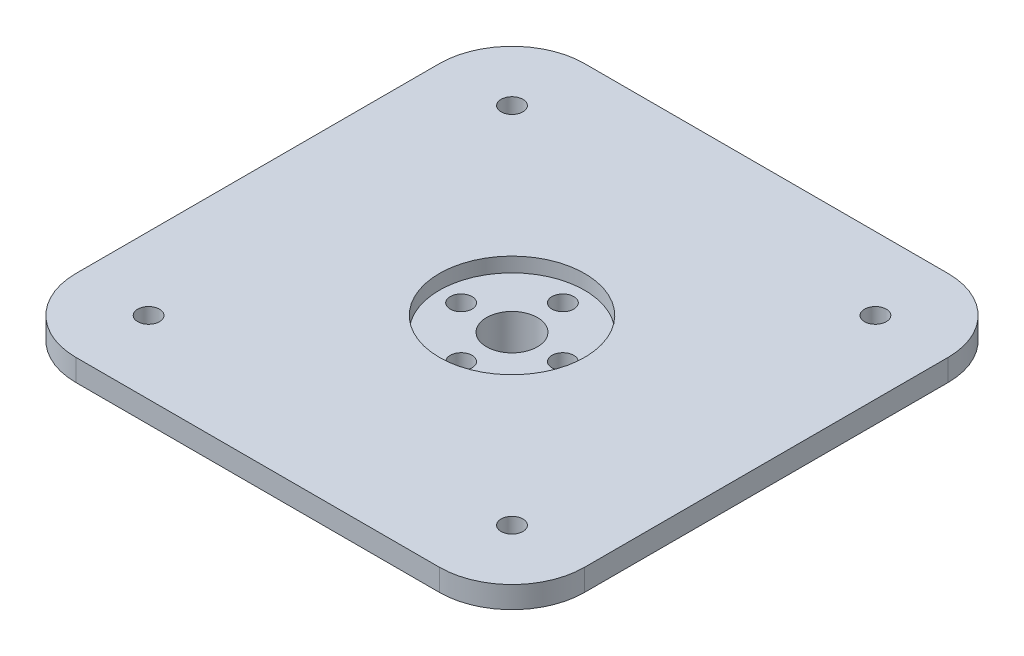
SolidWorks part; units mm, degrees
material "聚脂树脂"
ref_plane "前视基准面" through (0, 0, 0) normal (0, 0, 1) x (1, 0, 0)
ref_plane "上视基准面" through (0, 0, 0) normal (0, 1, 0) x (1, 0, 0)
ref_plane "右视基准面" through (0, 0, 0) normal (1, 0, 0) x (0, 0, -1)
other "Configuration Table"
sketch "草图1" plane through (0, 0, 0) normal (0, 1, 0) x (1, 0, 0)
  line L0 (0, 0) -> (36.9982, 0) construction
  line L1 (-35, -35) -> (35, -35)
  line L2 (-35, -35) -> (-35, 35)
  line L3 (-35, 35) -> (35, 35)
  line L4 (35, -35) -> (35, 35)
  line L5 (-35, -35) -> (35, 35) construction
  line L6 (-35, 35) -> (35, -35) construction
  line L7 (0, 0) -> (0, 22.4322) construction
  line L8 (0, 5) -> (42.8218, 5) construction
  circle A0 centre (0, 7) radius 1.5
  circle A1 centre (7, 0) radius 1.5
  circle A2 centre (0, 0) radius 3.5
  circle A3 centre (0, -7) radius 1.5
  circle A4 centre (-7, 0) radius 1.5
  circle A5 centre (25, 25) radius 1.5
  circle A11 centre (-25, 25) radius 1.5
  circle A12 centre (25, -25) radius 1.5
  circle A13 centre (-25, -25) radius 1.5
  point P0 (0, 0)
  dimension "D3" = 3
  dimension "D4" = 3
  dimension "D7" = 7
  dimension "D8" = 3
  dimension "D9" = 25
  dimension "D10" = 20
  dimension "D12" = 3
  dimension "D13" = 50
  dimension "D1" = 70
  dimension "D2" = 70
  dimension "D5" = 7
  dimension "D6" = 7
  dimension "D11" = 5
  dimension "D14" = 30
extrude "凸台-拉伸1" add sketch "草图1" along normal blind 3
sketch "草图2" plane through (0, 0, 0) normal (0, -1, 0) x (1, 0, 0)
  line L4 (35, -35) -> (35, 35)
  line L5 (35, 35) -> (-35, 35)
  line L6 (-35, 35) -> (-35, -35)
  line L7 (-35, -35) -> (35, -35)
  line L8 (35, -35) -> (35, 35)
  line L9 (35, 35) -> (-35, 35)
  line L10 (-35, 35) -> (-35, -35)
  line L11 (-35, -35) -> (35, -35)
  circle A0 centre (0, -7) radius 1.5 construction
  circle A1 centre (0, -7) radius 1.5
  circle A2 centre (-7, 0) radius 1.5 construction
  circle A3 centre (-7, 0) radius 1.5
  circle A4 centre (7, 0) radius 1.5 construction
  circle A5 centre (0, 7) radius 1.5 construction
  circle A6 centre (7, 0) radius 1.5
  circle A7 centre (0, 7) radius 1.5
  circle A8 centre (0, 0) radius 15
  circle A9 centre (0, 0) radius 3.5 construction
  circle A10 centre (0, 0) radius 3.5
  circle M6 centre (0, 7) radius 1.5
  circle M7 centre (7, 0) radius 1.5
  circle M12 centre (0, -7) radius 1.5
  circle M13 centre (0, 0) radius 3.5
  circle M14 centre (-7, 0) radius 1.5
  dimension "D2" = 30
  dimension "D1" = 0
extrude "凸台-拉伸2" add sketch "草图2" along normal blind 7 contours A8 M6 M13 M14 M12 M7
sketch "草图6" plane through (0, 0, 0) normal (0, -1, 0) x (1, 0, 0)
  circle A0 centre (0, 0) radius 15
  circle A1 centre (0, 0) radius 22
  dimension "D1" = 30
  dimension "D2" = 44
extrude "凸台-拉伸3" add sketch "草图6" along normal blind 9
sketch "草图8" plane through (0, 0, 0) normal (0, -1, 0) x (1, 0, 0)
  circle A0 centre (0, 0) radius 32
  circle A1 centre (0, 0) radius 12
  dimension "D1" = 24
  dimension "D2" = 64
extrude "凸台-拉伸5" add sketch "草图8" along normal blind 2
sketch "草图10" plane through (0, 3, 0) normal (0, 1, 0) x (1, 0, 0)
  line L0 (-35, 30) -> (-35, 35)
  line L1 (-35, 35) -> (-35, -35) construction
  line L2 (-35, 35) -> (35, 35)
  line L3 (35, 35) -> (35, 30)
  line L4 (35, -35) -> (35, 35) construction
  line L5 (35, 30) -> (-35, 30)
  dimension "D1" = 5
fillet "圆角1" radius 10 4 edges at (35, 1.5, -35) (35, 1.5, 35) (-35, 1.5, 35) (-35, 1.5, -35)
sketch "草图11" plane through (0, 3, 0) normal (0, 1, 0) x (1, 0, 0)
  circle A0 centre (0, 0) radius 10
  dimension "D1" = 20
extrude "切除-拉伸1" cut sketch "草图11" against normal blind 2
